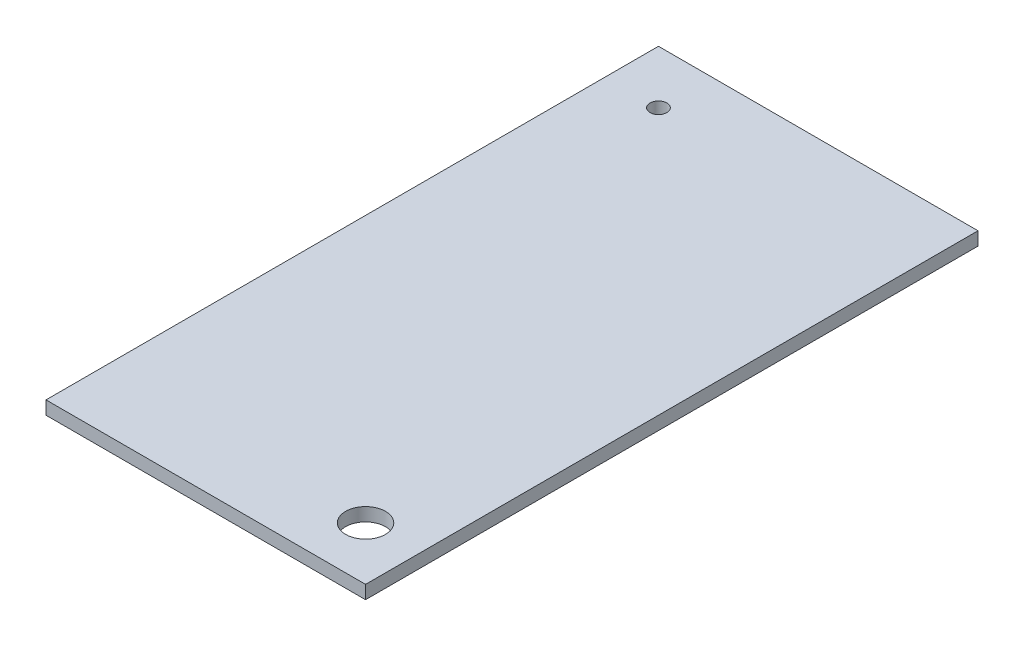
SolidWorks part; units mm, degrees
ref_plane "Front Plane" through (0, 0, 0) normal (0, 0, 1) x (1, 0, 0)
ref_plane "Top Plane" through (0, 0, 0) normal (0, 1, 0) x (1, 0, 0)
ref_plane "Right Plane" through (0, 0, 0) normal (1, 0, 0) x (0, 0, -1)
sketch "Sketch1" plane through (0, 0, 0) normal (0, 1, 0) x (1, 0, 0)
  line L1 (0, 0) -> (76.2, 0)
  line L2 (0, 0) -> (0, 146.05)
  line L3 (0, 146.05) -> (76.2, 146.05)
  line L4 (76.2, 0) -> (76.2, 146.05)
  circle A0 centre (63.5, 12.7) radius 4.7625
  circle A1 centre (12.7, 133.35) radius 2
  dimension "D3" = 12.7
  dimension "D4" = 12.7
  dimension "D7" = 4
  dimension "D1" = 146.05
  dimension "D2" = 76.2
  dimension "D5" = 12.7
  dimension "D6" = 12.7
extrude "Boss-Extrude1" add sketch "Sketch1" along normal blind 3.175
